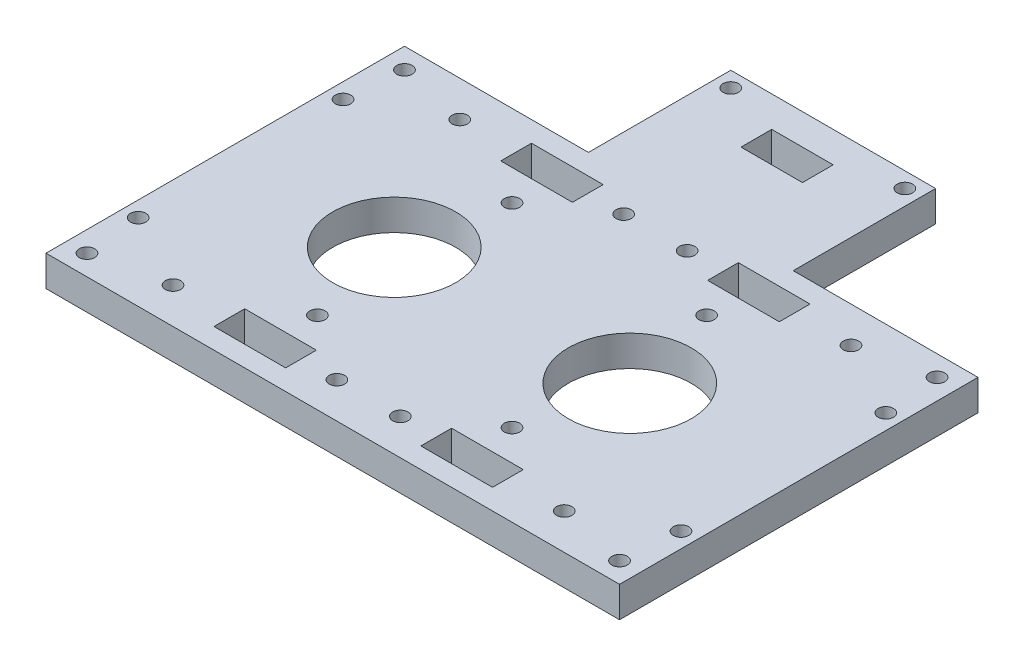
SolidWorks part; units mm, degrees
ref_plane "Front Plane" through (0, 0, 0) normal (0, 0, 1) x (1, 0, 0)
ref_plane "Top Plane" through (0, 0, 0) normal (0, 1, 0) x (1, 0, 0)
ref_plane "Right Plane" through (0, 0, 0) normal (1, 0, 0) x (0, 0, -1)
sketch "Sketch1" plane through (0, 0, 0) normal (0, 1, 0) x (1, 0, 0)
  line L0 (0, 0) -> (0, 14.7049) construction
  line L2 (-56, 63) -> (56, 63)
  line L3 (-56, 63) -> (-56, -7)
  line L4 (-56, -7) -> (56, -7)
  line L5 (56, 63) -> (56, -7)
  circle A0 centre (-6.2, 0) radius 1.5
  circle A1 centre (-38.2, 0) radius 1.5
  circle A2 centre (-6.2, 56) radius 1.5
  circle A3 centre (-38.2, 56) radius 1.5
  circle A4 centre (6.2, 0) radius 1.5
  circle A5 centre (38.2, 0) radius 1.5
  circle A6 centre (6.2, 56) radius 1.5
  circle A7 centre (38.2, 56) radius 1.5
  dimension "D1" = 3
  dimension "D2" = 3
  dimension "D3" = 3
  dimension "D4" = 3
  dimension "D5" = 56
  dimension "D6" = 56
  dimension "D7" = 32
  dimension "D8" = 32
  dimension "D9" = 6.2
  dimension "D10" = 7
  dimension "D11" = 7
  dimension "D12" = 112
  dimension "D13" = 56
  dimension "D14" = 7
  dimension "D15" = 7
extrude "Boss-Extrude1" add sketch "Sketch1" along normal blind 6
sketch "Sketch2" plane through (0, 6, 0) normal (0, 1, 0) x (1, 0, 0)
  line L0 (-53, -7) -> (-53, 63) construction
  line L1 (-56, -7) -> (56, -7) construction
  line L2 (56, 63) -> (-56, 63) construction
  line L3 (53, 63) -> (53, -7) construction
  line L4 (-56, 63) -> (-56, -7) construction
  line L5 (56, -7) -> (56, 63) construction
  circle A0 centre (-53, 48) radius 1.5
  circle A1 centre (-53, 8) radius 1.5
  circle A2 centre (53, 8) radius 1.5
  circle A3 centre (53, 48) radius 1.5
  point P21 (-53, 28)
  point P22 (53, 28)
  dimension "D3" = 3
  dimension "D4" = 3
  dimension "D5" = 3
  dimension "D6" = 3
  dimension "D1" = 3
  dimension "D2" = 3
  dimension "D7" = 3
  dimension "D8" = 20
  dimension "D9" = 20
  dimension "D10" = 20
  dimension "D11" = 20
extrude "Cut-Extrude1" cut sketch "Sketch2" against normal through all
sketch "Sketch3" plane through (0, 6, 0) normal (0, 1, 0) x (1, 0, 0)
  line L0 (-56, 28) -> (56, 28) construction
  line L1 (-56, 63) -> (-56, -7) construction
  line L2 (56, -7) -> (56, 63) construction
  line L3 (0, 63) -> (0, -7) construction
  line L4 (56, 63) -> (-56, 63) construction
  line L5 (-56, -7) -> (56, -7) construction
  line L6 (13.2, 53) -> (27.2, 53)
  line L7 (13.2, -3) -> (27.2, -3)
  line L8 (13.2, -3) -> (13.2, 3)
  line L9 (13.2, 3) -> (27.2, 3)
  line L10 (27.2, -3) -> (27.2, 3)
  line L11 (27.2, 59) -> (27.2, 53)
  line L12 (13.2, 59) -> (27.2, 59)
  line L13 (13.2, 59) -> (13.2, 53)
  line L14 (-13.2, 3) -> (-27.2, 3)
  line L15 (-27.2, -3) -> (-27.2, 3)
  line L16 (-13.2, -3) -> (-27.2, -3)
  line L17 (-13.2, -3) -> (-13.2, 3)
  line L18 (-13.2, 59) -> (-13.2, 53)
  line L19 (-13.2, 59) -> (-27.2, 59)
  line L20 (-27.2, 59) -> (-27.2, 53)
  line L21 (-13.2, 53) -> (-27.2, 53)
  dimension "D1" = 14
  dimension "D2" = 6
  dimension "D3" = 10
  dimension "D4" = 42.8
extrude "Cut-Extrude2" cut sketch "Sketch3" against normal through all
sketch "Sketch4" plane through (0, 6, 0) normal (0, 1, 0) x (1, 0, 0)
  line L0 (0, -7) -> (0, 63) construction
  line L1 (-56, -7) -> (56, -7) construction
  line L2 (56, 63) -> (-56, 63) construction
  line L3 (-56, 28) -> (56, 28) construction
  line L4 (-56, 63) -> (-56, -7) construction
  line L5 (56, -7) -> (56, 63) construction
  circle A0 centre (19, 9) radius 1.5
  circle A1 centre (19, 47) radius 1.5
  circle A2 centre (-19, 47) radius 1.5
  circle A3 centre (-19, 9) radius 1.5
  dimension "D1" = 3
  dimension "D2" = 37
  dimension "D3" = 16
extrude "Cut-Extrude3" cut sketch "Sketch4" against normal through all
sketch "Sketch5" plane through (0, 6, 0) normal (0, 1, 0) x (1, 0, 0)
  line L0 (-56, 28) -> (56, 28) construction
  line L1 (-56, 63) -> (-56, -7) construction
  line L2 (56, -7) -> (56, 63) construction
  circle A0 centre (-23, 28) radius 12
  circle A1 centre (23, 28) radius 12
  dimension "D4" = 24
  dimension "D5" = 24
  dimension "D1" = 112
  dimension "D2" = 33
  dimension "D3" = 33
extrude "Cut-Extrude4" cut sketch "Sketch5" against normal through all
sketch "Sketch6" plane through (0, 6, 0) normal (0, 1, 0) x (1, 0, 0)
  line L0 (56, 63) -> (-56, 63) construction
  line L1 (-56, 63) -> (-56, -7) construction
  line L2 (-56, 28) -> (56, 28) construction
  line L3 (56, -7) -> (56, 63) construction
  line L4 (0, 63) -> (0, -7) construction
  line L5 (-56, -7) -> (56, -7) construction
  circle A0 centre (-52, 59) radius 1.5
  circle A1 centre (52, 59) radius 1.5
  circle A2 centre (52, -3) radius 1.5
  circle A3 centre (-52, -3) radius 1.5
  dimension "D1" = 3
  dimension "D2" = 4
  dimension "D3" = 4
extrude "Cut-Extrude5" cut sketch "Sketch6" against normal blind 10
sketch "Sketch7" plane through (0, 0, 0) normal (0, 1, 0) x (1, 0, 0)
  line L0 (56, 63) -> (-56, 63) construction
  line L1 (-20.0794, 63) -> (19.9206, 63)
  line L2 (-20.0794, 63) -> (-20.0794, 90.8)
  line L3 (-20.0794, 90.8) -> (19.9206, 90.8)
  line L4 (19.9206, 63) -> (19.9206, 90.8)
  point P6 (-0.0794, 63)
  dimension "D1" = 20
  dimension "D2" = 40
  dimension "D3" = 27.8
extrude "Boss-Extrude2" add sketch "Sketch7" along normal blind 6 contours L3 L4 L1 L2
sketch "Sketch8" plane through (0, 6, 0) normal (0, 1, 0) x (1, 0, 0)
  line L0 (-20.0794, 90.8) -> (19.9206, 90.8) construction
  line L1 (-6.0794, 84.8) -> (5.9206, 84.8)
  line L2 (-6.0794, 84.8) -> (-6.0794, 78.8)
  line L3 (-6.0794, 78.8) -> (5.9206, 78.8)
  line L4 (5.9206, 84.8) -> (5.9206, 78.8)
  point P6 (-0.0794, 90.8)
  dimension "D1" = 6
  dimension "D2" = 12
  dimension "D3" = 6
  dimension "D4" = 6
extrude "Cut-Extrude6" cut sketch "Sketch8" against normal blind 6
sketch "Sketch9" plane through (0, 6, 0) normal (0, 1, 0) x (1, 0, 0)
  line L0 (-20.0794, 63) -> (-20.0794, 90.8) construction
  line L1 (-20.0794, 90.8) -> (19.9206, 90.8) construction
  line L2 (19.9206, 63) -> (19.9206, 90.8) construction
  circle A0 centre (-17.0794, 87.8) radius 1.5
  circle A1 centre (16.9206, 87.8) radius 1.5
  dimension "D1" = 3
  dimension "D2" = 3
  dimension "D3" = 3
  dimension "D4" = 3
  dimension "D5" = 3
  dimension "D6" = 3
extrude "Cut-Extrude7" cut sketch "Sketch9" against normal blind 6
